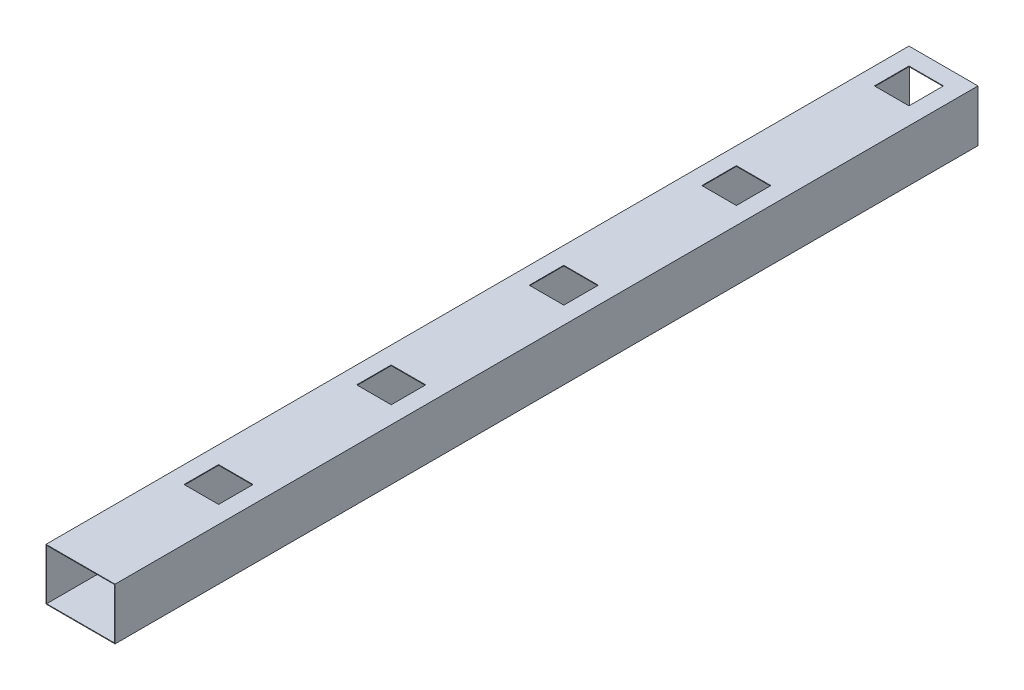
SolidWorks part; units mm, degrees
ref_plane "정면" through (0, 0, 0) normal (0, 0, 1) x (1, 0, 0)
ref_plane "윗면" through (0, 0, 0) normal (0, 1, 0) x (1, 0, 0)
ref_plane "우측면" through (0, 0, 0) normal (1, 0, 0) x (0, 0, -1)
sketch "스케치1" plane through (0, 0, 0) normal (0, 0, 1) x (1, 0, 0)
  line L0 (-39.3, 29.3) -> (39.3, 29.3)
  line L1 (-40, 30) -> (40, 30)
  line L2 (-40, 30) -> (-40, -30)
  line L3 (-40, -30) -> (40, -30)
  line L4 (40, 30) -> (40, -30)
  line L5 (-40, 30) -> (40, -30) construction
  line L6 (-40, -30) -> (40, 30) construction
  line L7 (39.3, 29.3) -> (39.3, -29.3)
  line L8 (-39.3, -29.3) -> (39.3, -29.3)
  line L9 (-39.3, 29.3) -> (-39.3, -29.3)
  point P0 (0, 0)
  dimension "D1" = 80
  dimension "D2" = 60
  dimension "D3" = 0.7
extrude "보스-돌출1" add sketch "스케치1" along normal blind 1000
sketch "스케치2" plane through (0, 30, 0) normal (0, 1, 0) x (1, 0, 0)
  line L0 (0, 0) -> (0, -1000) construction
  line L1 (-20, -20) -> (20, -20)
  line L2 (-20, -20) -> (-20, -60)
  line L3 (-20, -60) -> (20, -60)
  line L4 (20, -20) -> (20, -60)
  line L5 (-20, -20) -> (20, -60) construction
  line L6 (-20, -60) -> (20, -20) construction
  line L7 (40, -1000) -> (-40, -1000) construction
  point P0 (0, -40)
  dimension "D1" = 40
  dimension "D2" = 40
extrude "컷-돌출1" cut sketch "스케치2" against normal up to next contours L2 L1 L4 L3
pattern_linear "선형 패턴1" count 5 spacing 200 along (0, 0, 1) of "컷-돌출1"
